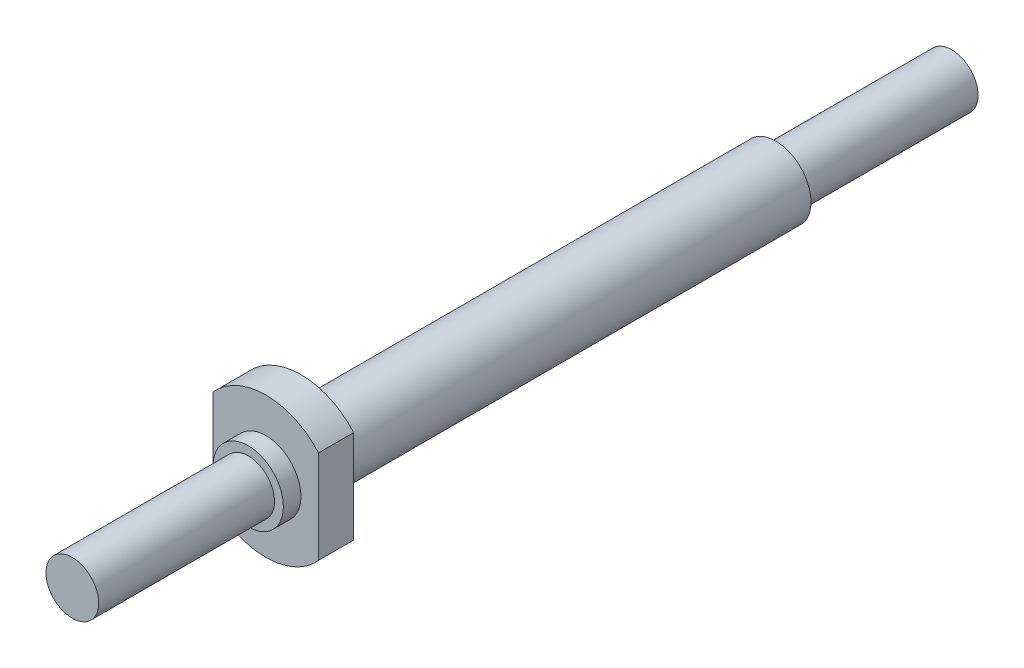
SolidWorks part; units mm, degrees
ref_plane "前视基准面" through (0, 0, 0) normal (0, 0, 1) x (1, 0, 0)
ref_plane "上视基准面" through (0, 0, 0) normal (0, 1, 0) x (1, 0, 0)
ref_plane "右视基准面" through (0, 0, 0) normal (1, 0, 0) x (0, 0, -1)
sketch "草图1" plane through (0, 0, 0) normal (0, 0, 1) x (1, 0, 0)
  line L2 (-3, 2.6458) -> (-3, -2.6458)
  line L4 (3, 2.6458) -> (3, -2.6458)
  arc A0 (-3, -2.6458) -> (3, -2.6458) centre (0, 0) ccw
  arc A1 (3, 2.6458) -> (-3, 2.6458) centre (0, 0) ccw
  dimension "D1" = 8
  dimension "D2" = 6
  dimension "D3" = 3
extrude "凸台-拉伸1" add sketch "草图1" along normal blind 2
sketch "草图2" plane through (0, 0, 2) normal (0, 0, 1) x (1, 0, 0)
  circle A0 centre (0, 0) radius 2
  dimension "D1" = 4
extrude "凸台-拉伸2" add sketch "草图2" along normal blind 1
sketch "草图3" plane through (0, 0, 3) normal (0, 0, 1) x (1, 0, 0)
  circle A0 centre (0, 0) radius 1.5
  dimension "D1" = 3
extrude "凸台-拉伸3" add sketch "草图3" along normal blind 10
cosmetic thread "装饰螺纹线5" parameters "D1"=10, "D2"=2.5
sketch "草图4" plane through (0, 0, 0) normal (0, 0, -1) x (-1, 0, 0)
  circle A0 centre (0, 0) radius 2
  dimension "D1" = 4
extrude "凸台-拉伸4" add sketch "草图4" along normal blind 27
sketch "草图5" plane through (0, 0, -27) normal (0, 0, -1) x (-1, 0, 0)
  circle A0 centre (0, 0) radius 1.5
  dimension "D1" = 3
extrude "凸台-拉伸5" add sketch "草图5" along normal blind 10
cosmetic thread "装饰螺纹线6" parameters "D1"=10, "D2"=2.5
